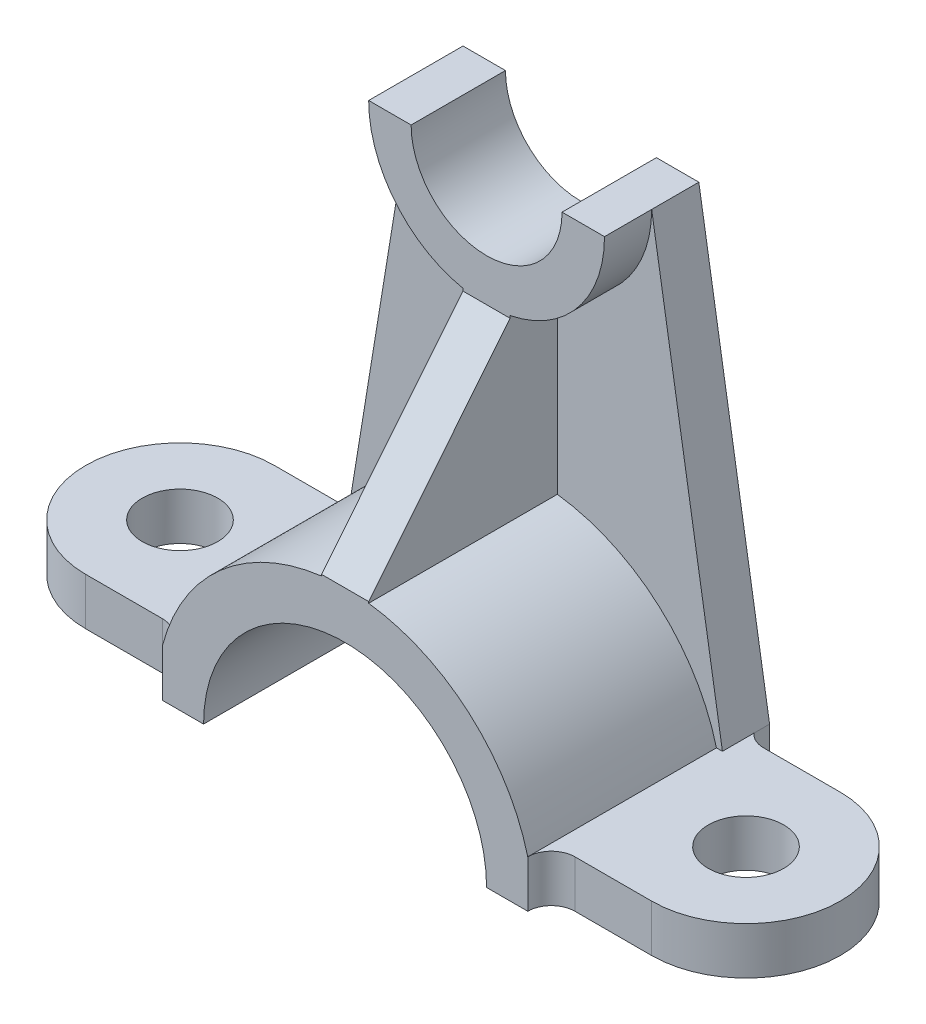
SolidWorks part; units mm, degrees
ref_plane "Front Plane" through (0, 0, 0) normal (0, 0, 1) x (1, 0, 0)
ref_plane "Top Plane" through (0, 0, 0) normal (0, 1, 0) x (1, 0, 0)
ref_plane "Right Plane" through (0, 0, 0) normal (1, 0, 0) x (0, 0, -1)
sketch "Sketch1" plane through (0, 0, 0) normal (0, 0, 1) x (1, 0, 0)
  line L0 (-40, 0) -> (-30, 0)
  line L1 (30, 0) -> (40, 0)
  arc A0 (40, 0) -> (-40, 0) centre (0, 0) ccw
  arc A1 (30, 0) -> (-30, 0) centre (0, 0) ccw
  dimension "D1" = 80
  dimension "D2" = 60
extrude "Boss-Extrude1" add sketch "Sketch1" against normal blind 40
sketch "Sketch2" plane through (0, 0, 0) normal (1, 0, 0) x (0, 0, -1)
  line L1 (0, 0) -> (50, 0)
  line L2 (0, 0) -> (0, 10)
  line L3 (0, 10) -> (50, 10)
  line L4 (50, 0) -> (50, 10)
  point P5 (44.7557, 10.2442)
  dimension "D1" = 10
  dimension "D2" = 50
extrude "Boss-Extrude2" add sketch "Sketch2" against normal up to surface (40 mm away) from offset 80
sketch "Sketch3" plane through (0, 10, 0) normal (0, 1, 0) x (1, 0, 0)
  line L0 (38.7298, 25) -> (80, 25) construction
  line L1 (38.7298, 0) -> (38.7298, 40) construction
  line L4 (38.7298, 50) -> (38.7298, 0)
  line L5 (43.7298, 5) -> (60, 5)
  line L6 (43.7298, 45) -> (60, 45)
  line L7 (80, 50) -> (80, 0) construction
  arc A0 (38.7298, 0) -> (43.7298, 5) centre (43.7298, 0) cw
  arc A1 (60, 5) -> (60, 45) centre (60, 25) ccw
  arc A2 (38.7298, 50) -> (43.7298, 45) centre (43.7298, 50) ccw
  point P4 (-77.4406, 47.6496)
  line M5 (38.7298, 0) -> (80, 0)
  line M6 (80, 0) -> (80, 50)
  line M7 (80, 50) -> (38.7298, 50)
  dimension "D2" = 20
  dimension "D3" = 20
  dimension "D1" = 5
extrude "Cut-Extrude6" cut sketch "Sketch3" along normal up to surface (10 mm away) from offset 10 contours A1 L5 A0 M5 M6 | A2 L6 A1 M7 M6
mirror "Mirror1" about plane through (0, 0, 0) normal (1, 0, 0) of "Boss-Extrude2", "Cut-Extrude6"
sketch "Sketch4" plane through (0, 0, 0) normal (0, 1, 0) x (1, 0, 0)
  line L6 (-40, 40) -> (40, 40)
  line L7 (40, 40) -> (40, 50)
  line L8 (40, 50) -> (-40, 50)
  line L9 (-40, 50) -> (-40, 40)
  dimension "D1" = 10
extrude "Boss-Extrude4" add sketch "Sketch4" along normal blind 102
sketch "Sketch6" plane through (0, 0, -50) normal (0, 0, -1) x (-1, 0, 0)
  line L0 (-40, 0) -> (40, 0) construction
  line L1 (-30, 0) -> (30, 0)
  arc A0 (30, 0) -> (-30, 0) centre (0, 0) ccw
  dimension "D1" = 30
extrude "Cut-Extrude7" cut sketch "Sketch6" against normal up to next
sketch "Sketch7" plane through (0, 0, -40) normal (0, 0, 1) x (1, 0, 0)
  line L0 (0, 102) -> (0, 40) construction
  line L1 (-40, 102) -> (40, 102) construction
  line L2 (-25, 102) -> (-16, 102)
  line L3 (16, 102) -> (25, 102)
  arc A0 (38.7298, 10) -> (-38.7298, 10) centre (0, 0) ccw construction
  arc A1 (-16, 102) -> (16, 102) centre (0, 102) ccw
  arc A2 (-25, 102) -> (25, 102) centre (0, 102) ccw
  dimension "D1" = 16
  dimension "D2" = 25
extrude "Boss-Extrude5" add sketch "Sketch7" along normal blind 10
sketch "Sketch8" plane through (0, 0, -40) normal (0, 0, 1) x (1, 0, 0)
  line L0 (16, 102) -> (-16, 102)
  line L1 (-25, 102) -> (-40, 102)
  line L2 (-40, 102) -> (-40, 10)
  line L3 (-40, 10) -> (-25, 102)
  line L4 (25, 102) -> (40, 102)
  line L5 (40, 102) -> (40, 10)
  line L6 (43.7298, 10) -> (38.7298, 10) construction
  line L7 (40, 102) -> (40, 10) construction
  line L8 (40, 10) -> (25, 102)
  arc A0 (-16, 102) -> (16, 102) centre (0, 102) ccw
extrude "Cut-Extrude8" cut sketch "Sketch8" against normal blind 10
sketch "Sketch9" plane through (0, 10, 0) normal (0, 1, 0) x (1, 0, 0)
  circle A0 centre (60, 25) radius 8
  arc A1 (60, 5) -> (60, 45) centre (60, 25) ccw construction
  dimension "D1" = 16
extrude "Cut-Extrude9" cut sketch "Sketch9" against normal up to next
mirror "Mirror2" about plane through (0, 0, 0) normal (1, 0, 0) of "Cut-Extrude9"
sketch "Sketch11" plane through (0, 0, 0) normal (1, 0, 0) x (0, 0, -1)
  line L0 (0, 30) -> (0, 40)
  line L1 (0, 40) -> (30, 77)
  line L2 (30, 77) -> (30, 86)
  line L3 (30, 86) -> (40, 86)
  line L4 (40, 102) -> (40, 10) construction
  line L5 (40, 86) -> (40, 30)
  line L6 (50, 30) -> (0, 30) construction
  line L7 (40, 30) -> (0, 30)
extrude "Boss-Extrude6" add sketch "Sketch11" along normal mid plane 10
